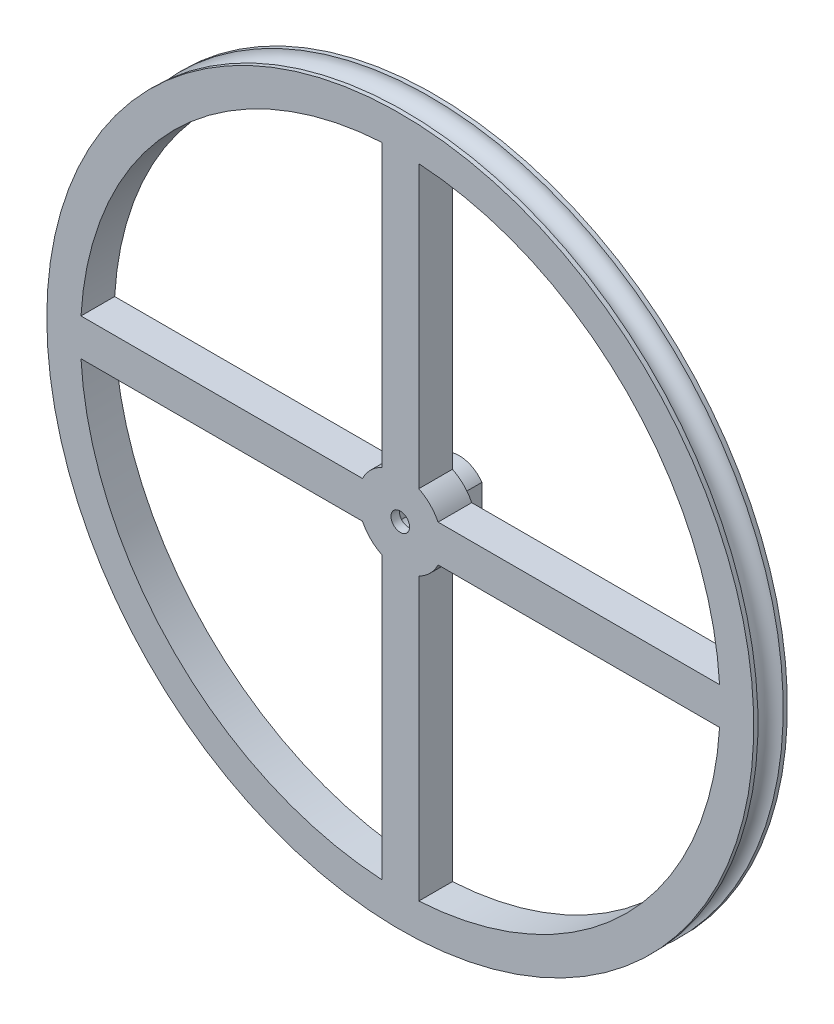
SolidWorks part; units mm, degrees
ref_plane "Front Plane" through (0, 0, 0) normal (0, 0, 1) x (1, 0, 0)
ref_plane "Top Plane" through (0, 0, 0) normal (0, 1, 0) x (1, 0, 0)
ref_plane "Right Plane" through (0, 0, 0) normal (1, 0, 0) x (0, 0, -1)
sketch "Sketch1" plane through (0, 0, 0) normal (0, 1, 0) x (1, 0, 0)
  line L0 (-53.34, 0) -> (-53.34, -0.635)
  line L1 (0, 0) -> (-53.34, 0)
  line L2 (0, 0) -> (0, -5.08)
  line L3 (0, -5.08) -> (-53.34, -5.08)
  line L4 (-53.34, 0) -> (-53.34, -5.08) construction
  line L5 (-53.34, -4.445) -> (-53.34, -5.08)
  circle A0 centre (-53.34, -2.54) radius 1.905 construction
  arc A1 (-53.34, -0.635) -> (-53.34, -4.445) centre (-53.34, -2.54) cw
  dimension "D3" = 1.905
  dimension "D1" = 53.34
  dimension "D2" = 5.08
revolve "Revolve1" add sketch "Sketch1" angle 360 about L2
sketch "Sketch3" plane through (0, 0, 0) normal (0, 0, -1) x (-1, 0, 0)
  line L18 (-2.794, 48.1791) -> (-2.794, 5.7023) construction
  line L19 (-2.794, 5.7023) -> (2.794, 5.7023) construction
  line L20 (2.794, 5.7023) -> (2.794, 48.1791) construction
  line L21 (2.794, 48.1791) -> (-2.794, 48.1791) construction
  line L22 (48.7183, -2.794) -> (48.7183, 2.794) construction
  line L23 (48.7183, 2.794) -> (6.2416, 2.794) construction
  line L24 (2.794, -6.2416) -> (-2.794, -6.2416) construction
  line L25 (6.2416, -2.794) -> (48.7183, -2.794) construction
  line L26 (6.2416, 2.794) -> (6.2416, -2.794) construction
  line L27 (-2.2547, -48.7183) -> (3.3333, -48.7183) construction
  line L28 (3.3333, -48.7183) -> (3.3333, -6.2416) construction
  line L29 (-2.2547, -6.2416) -> (-2.2547, -48.7183) construction
  line L30 (3.3333, -6.2416) -> (-2.2547, -6.2416) construction
  line L31 (-48.1791, 2.2547) -> (-48.1791, -3.3333) construction
  line L32 (-48.1791, -3.3333) -> (-5.7023, -3.3333) construction
  line L33 (-5.7023, 2.2547) -> (-48.1791, 2.2547) construction
  line L34 (-5.7023, -3.3333) -> (-5.7023, 2.2547) construction
  line L35 (2.794, 48.1791) -> (2.794, 5.7023)
  line L36 (5.7023, 2.794) -> (48.1791, 2.794)
  line L37 (2.794, -5.7023) -> (2.794, -48.1791)
  line L38 (48.1791, -2.794) -> (5.7023, -2.794)
  line L39 (-6.2416, -2.794) -> (-6.2416, 2.794) construction
  line L40 (-5.7023, -2.794) -> (-48.1791, -2.794)
  line L41 (-2.794, -48.1791) -> (-2.794, -5.7023)
  line L42 (-2.794, 6.2416) -> (2.794, 6.2416) construction
  line L43 (-2.794, 5.7023) -> (-2.794, 48.1791)
  line L44 (-48.1791, 2.794) -> (-5.7023, 2.794)
  circle A4 centre (0, 0) radius 6.35 construction
  circle A5 centre (0, 0) radius 48.26 construction
  arc A6 (2.794, 48.1791) -> (48.1791, 2.794) centre (0, 0) cw
  arc A7 (2.794, 5.7023) -> (5.7023, 2.794) centre (0, 0) cw
  arc A8 (48.1791, -2.794) -> (2.794, -48.1791) centre (0, 0) cw
  arc A9 (5.7023, -2.794) -> (2.794, -5.7023) centre (0, 0) cw
  arc A10 (-2.794, -48.1791) -> (-48.1791, -2.794) centre (0, 0) cw
  arc A11 (-2.794, -5.7023) -> (-5.7023, -2.794) centre (0, 0) cw
  arc A12 (-48.1791, 2.794) -> (-2.794, 48.1791) centre (0, 0) cw
  arc A13 (-5.7023, 2.794) -> (-2.794, 5.7023) centre (0, 0) cw
  point P23 (0.2696, -0.2696)
  point P43 (0, 0)
  dimension "D1" = 5.588
  dimension "D2" = 4
  dimension "D3" = 12.7
  dimension "D5" = 48.26
  dimension "D6" = 2.794
  dimension "D4" = 4
extrude "Cut-Extrude2" cut sketch "Sketch3" against normal through all
sketch "Sketch6" plane through (0, 0, 0) normal (0, 0, -1) x (-1, 0, 0)
  line L0 (-2.159, 1.9675) -> (-2.159, -1.9675)
  line L1 (2.159, 1.9675) -> (2.159, -1.9675)
  circle A0 centre (0, 0) radius 2.921 construction
  arc A1 (-2.159, -1.9675) -> (2.159, -1.9675) centre (0, 0) ccw
  arc A2 (2.159, 1.9675) -> (-2.159, 1.9675) centre (0, 0) ccw
  dimension "D1" = 4.318
  dimension "D3" = 5.842
  dimension "D2" = 2.159
extrude "Cut-Extrude3" cut sketch "Sketch6" against normal through all
sketch "Sketch7" plane through (0, 0, 0) normal (0, 0, -1) x (-1, 0, 0)
  line L4 (3.429, -2.4097) -> (3.429, 2.4097)
  line L5 (-3.429, 2.4097) -> (-3.429, -2.4097)
  line L6 (3.429, -2.4097) -> (3.429, 2.4097)
  line L7 (-3.429, 2.4097) -> (-3.429, -2.4097)
  line L10 (2.159, -1.9675) -> (2.159, 1.9675)
  line L11 (-2.159, 1.9675) -> (-2.159, -1.9675)
  line L12 (2.159, -1.9675) -> (2.159, 1.9675)
  line L13 (-2.159, 1.9675) -> (-2.159, -1.9675)
  arc A4 (-3.429, -2.4097) -> (3.429, -2.4097) centre (0, 0) ccw
  arc A5 (3.429, 2.4097) -> (-3.429, 2.4097) centre (0, 0) ccw
  arc A6 (-3.429, -2.4097) -> (3.429, -2.4097) centre (0, 0) ccw
  arc A7 (3.429, 2.4097) -> (-3.429, 2.4097) centre (0, 0) ccw
  arc A10 (-2.159, -1.9675) -> (2.159, -1.9675) centre (0, 0) ccw
  arc A11 (2.159, 1.9675) -> (-2.159, 1.9675) centre (0, 0) ccw
  arc A12 (-2.159, -1.9675) -> (2.159, -1.9675) centre (0, 0) ccw
  arc A13 (2.159, 1.9675) -> (-2.159, 1.9675) centre (0, 0) ccw
  dimension "D1" = 1.27
  dimension "D2" = 0
extrude "Boss-Extrude1" add sketch "Sketch7" along normal blind 3.81
sketch "Sketch8" plane through (0, 0, 5.08) normal (0, 0, 1) x (1, 0, 0)
  circle A0 centre (0, 0) radius 1.397
  circle A1 centre (0, 0) radius 3.81
  dimension "D1" = 2.794
extrude "Boss-Extrude2" add sketch "Sketch8" against normal blind 1.27
